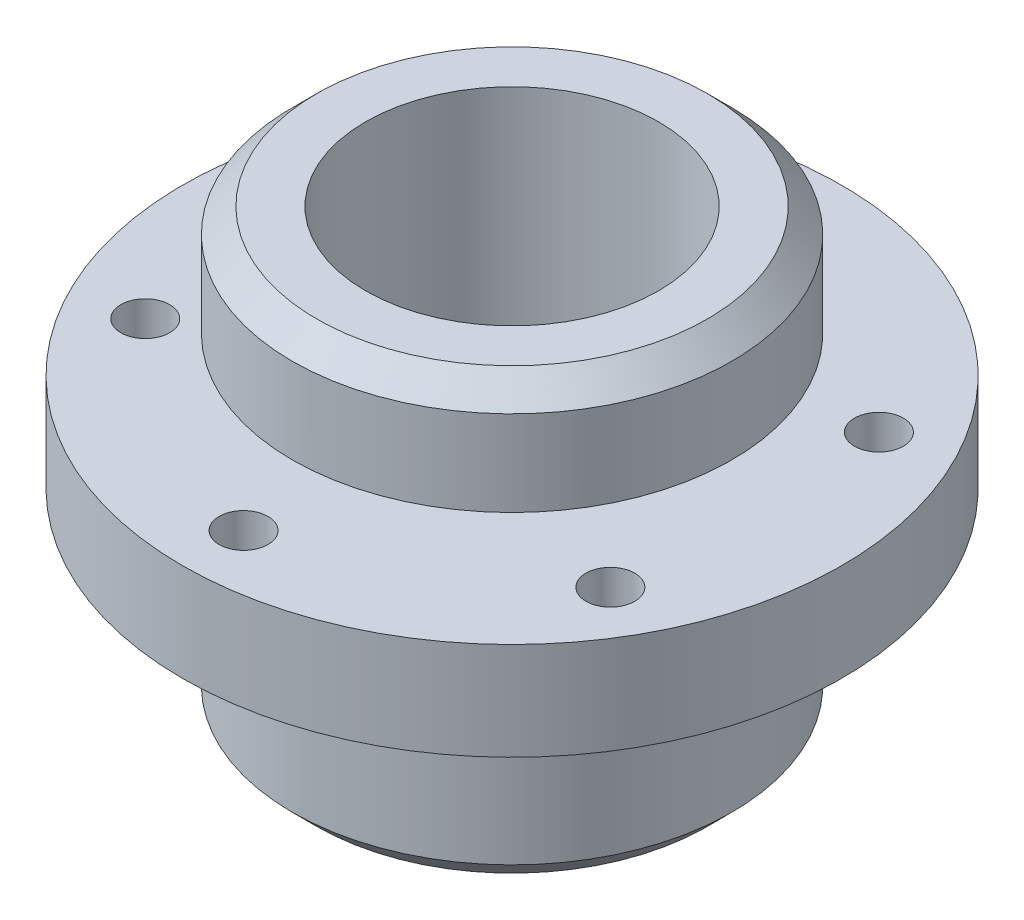
SolidWorks part; units mm, degrees
ref_plane "Front Plane" through (0, 0, 0) normal (0, 0, 1) x (1, 0, 0)
ref_plane "Top Plane" through (0, 0, 0) normal (0, 1, 0) x (1, 0, 0)
ref_plane "Right Plane" through (0, 0, 0) normal (1, 0, 0) x (0, 0, -1)
sketch "Sketch1" plane through (0, 0, 0) normal (0, 0, 1) x (1, 0, 0)
  line L0 (0, 63.408) -> (0, -63.408) construction
  line L1 (24, -46.7154) -> (36, -46.7154)
  line L2 (36, -46.7154) -> (36, -22.7154)
  line L3 (36, -22.7154) -> (27.1645, -22.7154)
  line L4 (27.1645, -22.7154) -> (27.1645, -14.7154)
  line L5 (27.1645, -14.7154) -> (54, -14.7154)
  line L6 (54, -14.7154) -> (54, 1.2846)
  line L7 (54, 1.2846) -> (27.1645, 1.2846)
  line L8 (27.1645, 1.2846) -> (27.1645, 7.2846)
  line L9 (27.1645, 7.2846) -> (36, 7.2846)
  line L10 (36, 7.2846) -> (36, 25.2846)
  line L11 (36, 25.2846) -> (24, 25.2846)
  line L12 (24, 25.2846) -> (24, -46.7154)
  point P4 (0, 0)
  point P8 (0, -46.7154)
  dimension "D1" = 36
  dimension "D2" = 32
  dimension "D3" = 8
  dimension "D4" = 16
  dimension "D5" = 54
  dimension "D6" = 6
  dimension "D8" = 24
revolve "Revolve1" add sketch "Sketch1" angle 360 about L0
sketch "Sketch2" plane through (0, 1.2846, 0) normal (0, 1, 0) x (1, 0, 0)
  line L0 (0, 0) -> (0, 54) construction
  circle A0 centre (0, 0) radius 54 construction
  circle A1 centre (0, 44) radius 4
  dimension "D2" = 8
  dimension "D1" = 44
extrude "Cut-Extrude1" cut sketch "Sketch2" against normal up to surface (16 mm away) up to face at (0, -14.7154, 54)
pattern_circular "CirPattern1" count 6 every 60 about axis through (0, 0, 0) along (0, 1, 0) of "Cut-Extrude1"
chamfer "Chamfer1" distance 4 angle 45 1 edges at (0, 25.2846, 36)
chamfer "Chamfer2" distance 4 angle 45 1 edges at (0, -46.7154, 36)
fillet "Fillet1" radius 4 1 edges at (0, -22.7154, 27.1645)
fillet "Fillet2" radius 4 1 edges at (0, 7.2846, 27.1645)
